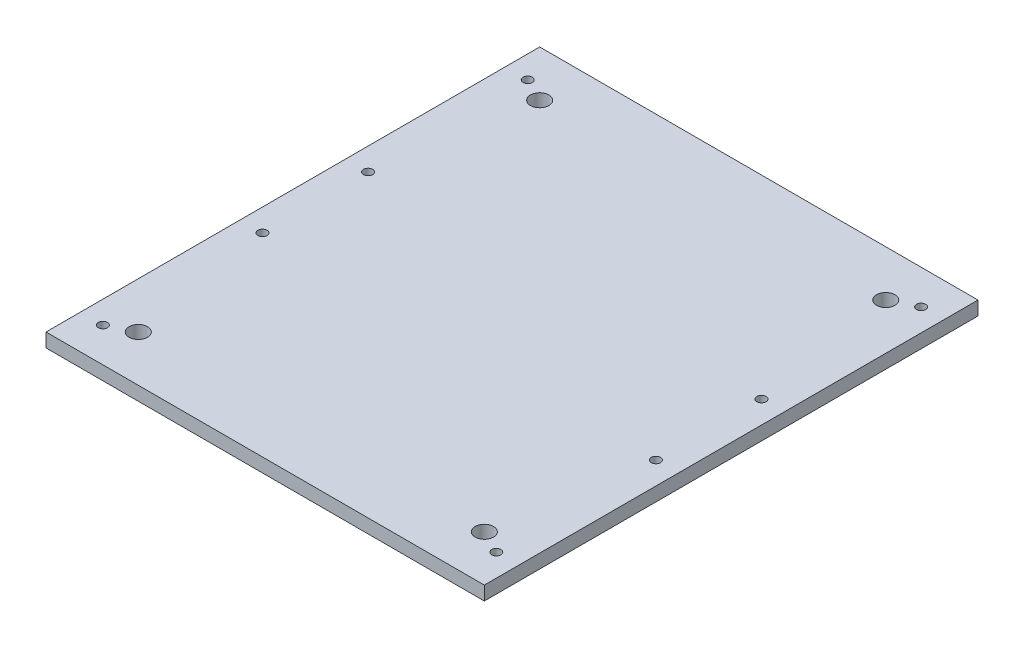
SolidWorks part; units mm, degrees
ref_plane "Front Plane" through (0, 0, 0) normal (0, 0, 1) x (1, 0, 0)
ref_plane "Top Plane" through (0, 0, 0) normal (0, 1, 0) x (1, 0, 0)
ref_plane "Right Plane" through (0, 0, 0) normal (1, 0, 0) x (0, 0, -1)
sketch "Sketch2" plane through (0, 0, 0) normal (0, 1, 0) x (1, 0, 0)
  line L0 (37.5, -43.5) -> (47.5, -43.5)
  line L1 (-47.5, -53.5) -> (47.5, -53.5)
  line L2 (-47.5, -53.5) -> (-47.5, 53.5)
  line L3 (-47.5, 53.5) -> (47.5, 53.5)
  line L4 (47.5, -53.5) -> (47.5, 53.5)
  line L5 (-47.5, -53.5) -> (47.5, 53.5) construction
  line L6 (-47.5, 53.5) -> (47.5, -53.5) construction
  line L7 (37.5, -43.5) -> (37.5, -53.5)
  line L8 (-55, 0) -> (55, 0) construction
  line L9 (0, -55) -> (0, 55) construction
  line L15 (-60, 66) -> (60, 66)
  line L16 (-60, 66) -> (-60, -66)
  line L17 (-60, -66) -> (60, -66)
  line L18 (60, 66) -> (60, -66)
  line L19 (-60, 66) -> (60, -66) construction
  line L20 (-60, -66) -> (60, 66) construction
  circle A1 centre (37.5, -43.5) radius 2
  circle A2 centre (37.5, 43.5) radius 2
  circle A3 centre (-37.5, -43.5) radius 2
  circle A4 centre (-37.5, 43.5) radius 2
  point P0 (0, 0)
  point P20 (0, 0)
  point P21 (0, 0)
  dimension "D3" = 10
  dimension "D5" = 4
  dimension "D1" = 95
  dimension "D2" = 107
  dimension "D4" = 10
  dimension "D6" = 120
  dimension "D7" = 132
extrude "Boss-Extrude1" add sketch "Sketch2" along normal blind 3 contours A1 L0 L4 L3 L2 L1 L7 A4 A2 A3 | A1 L7 L1 L4 L0
sketch "Sketch3" plane through (0, 3, 0) normal (0, 1, 0) x (1, 0, 0)
  line L5 (-47.515, 40.2371) -> (-32.4121, 40.2371) construction
  line L6 (-47.5, -53.5) -> (-47.5, 53.5) construction
  line L10 (-47.5, 17.2402) -> (-47.5, 40.2371)
  line L11 (-47.6, 40.3371) -> (-32.2822, 40.3371)
  line L12 (-32.2822, 40.3371) -> (-30.49, 37.2328)
  line L13 (-30.49, 17.1402) -> (-30.49, 37.2328)
  line L14 (-47.6, 17.1402) -> (-30.49, 17.1402)
  line L15 (-47.6, 17.1402) -> (-47.6, 40.3371)
  line L16 (-47.5, 40.2371) -> (-32.34, 40.2371) construction
  line L17 (-47.5, 17.2402) -> (-30.59, 17.2402) construction
  line L18 (-30.59, 17.2402) -> (-30.59, 37.206) construction
  line L19 (-32.34, 40.2371) -> (-30.59, 37.206) construction
  line L20 (0, 62.7045) -> (0, 59.4045) construction
  line L21 (32.2822, 40.3371) -> (30.49, 37.2328)
  line L22 (30.49, 17.1402) -> (30.49, 37.2328)
  line L23 (47.6, 17.1402) -> (30.49, 17.1402)
  line L24 (47.5, 17.2402) -> (47.5, 40.2371)
  line L25 (47.6, 40.3371) -> (32.2822, 40.3371)
  line L26 (-130.0965, 0) -> (-126.7965, 0) construction
  line L27 (47.5, -17.2402) -> (47.5, -40.2371)
  line L28 (47.6, -17.1402) -> (30.49, -17.1402)
  line L29 (30.49, -17.1402) -> (30.49, -37.2328)
  line L30 (32.2822, -40.3371) -> (30.49, -37.2328)
  line L31 (47.6, -40.3371) -> (32.2822, -40.3371)
  line L32 (-30.49, -17.1402) -> (-30.49, -37.2328)
  line L33 (-32.2822, -40.3371) -> (-30.49, -37.2328)
  line L34 (-47.6, -40.3371) -> (-32.2822, -40.3371)
  line L35 (-47.5, -17.2402) -> (-47.5, -40.2371)
  line L36 (-47.6, -17.1402) -> (-30.49, -17.1402)
  dimension "D1" = 0.1
sketch "Sketch6" plane through (0, 3, 0) normal (0, 1, 0) x (1, 0, 0)
  line L24 (-47.5, 53.5) -> (-47.5, -53.5)
  line L30 (-47.5, -53.5) -> (47.5, -53.5)
  line L31 (47.5, -53.5) -> (47.5, 53.5)
  line L42 (47.5, 53.5) -> (-47.5, 53.5)
  line L48 (-47.5, 53.5) -> (-47.5, -53.5)
  line L54 (-47.5, -53.5) -> (47.5, -53.5)
  line L55 (47.5, -53.5) -> (47.5, 53.5)
  line L66 (47.5, 53.5) -> (-47.5, 53.5)
  dimension "D1" = 0
sketch "Sketch7" plane through (0, 3, 0) normal (0, 1, 0) x (1, 0, 0)
  line L1 (47.5, 53.5) -> (-47.5, 53.5) construction
  line L2 (47.6, 40.3371) -> (32.2822, 40.3371) construction
  circle A0 centre (42.63, 46.04) radius 1
  point P6 (43.6424, 47.481)
  dimension "D3" = 2
  dimension "D1" = 5.7029
  dimension "D2" = 7.46
extrude "Cut-Extrude2" cut sketch "Sketch7" against normal blind 10
sketch "Sketch9" plane through (0, 3, 0) normal (0, 1, 0) x (1, 0, 0)
  line L0 (47.5, 28.7386) -> (10.5585, 28.7386)
  line L1 (47.5, 17.2402) -> (47.5, 40.2371) construction
ref_plane "Plane1" through (0, 0, -28.7386) normal (0, 0, -1) x (-1, 0, 0)
mirror "Mirror2" about plane through (0, 0, -28.7386) normal (0, 0, -1) of "Cut-Extrude2"
mirror "Mirror3" about plane through (0, 0, 0) normal (1, 0, 0) of "Cut-Extrude2", "Mirror2" second plane through (0, 0, 0) second plane normal (0, 0, 1)
